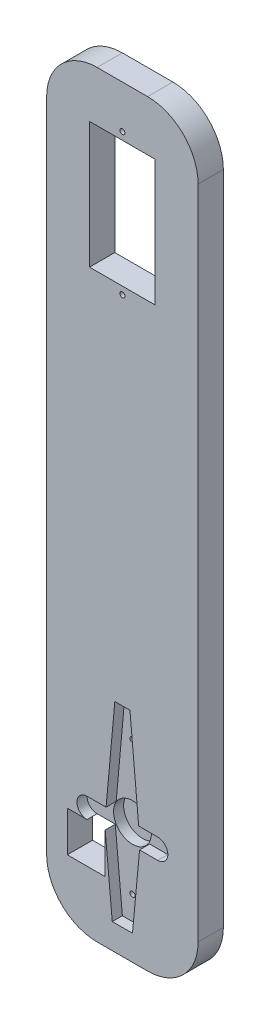
SolidWorks part; units mm, degrees
ref_plane "Přední rovina" through (0, 0, 0) normal (0, 0, 1) x (1, 0, 0)
ref_plane "Horní rovina" through (0, 0, 0) normal (0, 1, 0) x (1, 0, 0)
ref_plane "Pravá rovina" through (0, 0, 0) normal (1, 0, 0) x (0, 0, -1)
sketch "Skica1" plane through (0, 0, 0) normal (0, 0, 1) x (1, 0, 0)
  line L1 (0, 0) -> (30, 0)
  line L2 (0, 0) -> (0, 150)
  line L3 (0, 150) -> (30, 150)
  line L4 (30, 0) -> (30, 150)
  dimension "D1" = 150
  dimension "D2" = 30
extrude "Přidat vysunutím1" add sketch "Skica1" along normal blind 5
fillet "Zaoblit1" radius 10 4 edges at (30, 0, 2.5) (0, 0, 2.5) (30, 150, 2.5) (0, 150, 2.5)
sketch "Skica2" plane through (0, 0, 5) normal (0, 0, 1) x (1, 0, 0)
  line L1 (8.5, 140) -> (21.5, 140)
  line L2 (8.5, 140) -> (8.5, 115)
  line L3 (8.5, 115) -> (21.5, 115)
  line L4 (21.5, 140) -> (21.5, 115)
  line L5 (20, 150) -> (10, 150) construction
  point P4 (15, 150)
  point P7 (15, 140)
  dimension "D1" = 13
  dimension "D2" = 25
  dimension "D3" = 10
extrude "Odebrat vysunutím1" cut sketch "Skica2" against normal through all
sketch "Skica3" plane through (0, 0, 5) normal (0, 0, 1) x (1, 0, 0)
  line L0 (21.5, 140) -> (8.5, 140) construction
  line L2 (8.5, 140) -> (8.5, 115) construction
  line L3 (8.5, 127.5) -> (21.5, 127.5) construction
  line L4 (21.5, 115) -> (21.5, 140) construction
  circle A0 centre (15, 141.5) radius 0.5
  circle A1 centre (15, 113.5) radius 0.5
  point P4 (15, 140)
  point P9 (8.5, 127.5)
  dimension "D1" = 1
  dimension "D2" = 14
  dimension "D3" = 28
extrude "Odebrat vysunutím2" cut sketch "Skica3" against normal through all
sketch "Skica4" plane through (0, 0, 5) normal (0, 0, 1) x (1, 0, 0)
  line L0 (11.5, 21) -> (18.5, 21)
  line L1 (18.5, 21) -> (16.5, 43)
  line L3 (13.5, 43) -> (11.5, 21)
  line L4 (13.5, 43) -> (16.5, 43)
  line L5 (11.5, 21) -> (13, 5)
  line L6 (13, 5) -> (17, 5)
  line L7 (17, 5) -> (18.5, 21)
  line L8 (10, 0) -> (20, 0) construction
  line L10 (8, 24) -> (22, 24)
  line L11 (8, 24) -> (8, 20)
  line L12 (8, 20) -> (22, 20)
  line L13 (22, 24) -> (22, 20)
  arc A0 (8, 24) -> (8, 20) centre (8, 22) ccw
  arc A1 (22, 24) -> (22, 20) centre (22, 22) cw
  point P2 (15, 43)
  point P5 (15, 21)
  point P6 (15, 5)
  point P11 (15, 0)
  point P16 (15, 24)
  dimension "D1" = 7
  dimension "D2" = 3
  dimension "D3" = 22
  dimension "D4" = 16
  dimension "D5" = 5
  dimension "D6" = 4
  dimension "D7" = 19
  dimension "D8" = 14
  dimension "D9" = 4
extrude "Odebrat vysunutím3" cut sketch "Skica4" against normal blind 2 contours L12 L5 L6 L7 | L5 L12 L7 L0 | L11 L12 L5 L3 L10 | L10 L3 L0 L1 | L13 L10 L1 L7 L12 | A1 L13 | L11 A0 | L3 L10 L1 L4
sketch "Skica5" plane through (0, 0, 3) normal (0, 0, 1) x (1, 0, 0)
  line L0 (6, 22) -> (24, 22) construction
  line L1 (13.5, 43) -> (16.5, 43) construction
  circle A0 centre (15, 36.2) radius 0.5
  circle A1 centre (15, 9.7) radius 0.5
  arc A2 (8, 24) -> (8, 20) centre (8, 22) ccw construction
  arc A3 (22, 20) -> (22, 24) centre (22, 22) ccw construction
  point P10 (15, 43)
  dimension "D1" = 1
  dimension "D2" = 1
  dimension "D4" = 14.2
  dimension "D3" = 12.3
extrude "Odebrat vysunutím4" cut sketch "Skica5" against normal through all
sketch "Skica6" plane through (0, 0, 3) normal (0, 0, 1) x (1, 0, 0)
  line L0 (6, 22) -> (24, 22) construction
  line L1 (15, 43) -> (15, 5) construction
  line L2 (13.5, 43) -> (16.5, 43) construction
  line L3 (13, 5) -> (17, 5) construction
  circle A0 centre (15, 22) radius 3.75
  arc A1 (8, 24) -> (8, 20) centre (8, 22) ccw construction
  arc A2 (22, 20) -> (22, 24) centre (22, 22) ccw construction
  point P16 (15, 22)
  dimension "D2" = 7.5
  dimension "D1" = 0
extrude "Odebrat vysunutím5" cut sketch "Skica6" against normal blind 2
sketch "Skica7" plane through (0, 0, 5) normal (0, 0, 1) x (1, 0, 0)
  line L1 (11.5937, 20) -> (4.0937, 20)
  line L2 (11.5937, 20) -> (11.5938, 12)
  line L3 (11.5938, 12) -> (4.0938, 12)
  line L4 (4.0937, 20) -> (4.0938, 12)
  dimension "D1" = 8
  dimension "D2" = 7.5
extrude "Odebrat vysunutím6" cut sketch "Skica7" against normal through all
